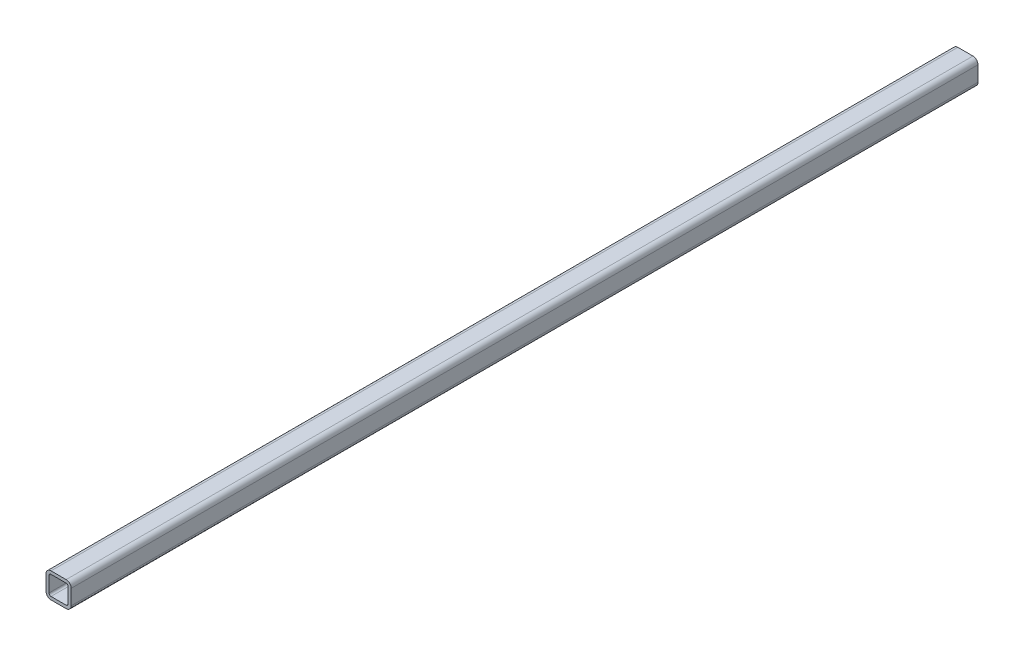
SolidWorks part; units mm, degrees
material "Plain Carbon Steel"
ref_plane "Front Plane" through (0, 0, 0) normal (0, 0, 1) x (1, 0, 0)
ref_plane "Top Plane" through (0, 0, 0) normal (0, 1, 0) x (1, 0, 0)
ref_plane "Right Plane" through (0, 0, 0) normal (1, 0, 0) x (0, 0, -1)
sketch "Sketch1" plane through (0, 0, 0) normal (0, 0, 1) x (1, 0, 0)
  line L0 (-9.5, 7.5) -> (-9.5, -7.5)
  line L1 (-7.5, -12.5) -> (7.5, -12.5)
  line L2 (-12.5, -7.5) -> (-12.5, 7.5)
  line L3 (-7.5, 12.5) -> (7.5, 12.5)
  line L4 (12.5, -7.5) -> (12.5, 7.5)
  line L5 (-12.5, -12.5) -> (12.5, 12.5) construction
  line L6 (-12.5, 12.5) -> (12.5, -12.5) construction
  line L7 (-7.5, -9.5) -> (7.5, -9.5)
  line L8 (9.5, -7.5) -> (9.5, 7.5)
  line L9 (7.5, 9.5) -> (-7.5, 9.5)
  arc A0 (-9.5, -7.5) -> (-7.5, -9.5) centre (-7.5, -7.5) ccw
  arc A1 (7.5, -9.5) -> (9.5, -7.5) centre (7.5, -7.5) ccw
  arc A2 (9.5, 7.5) -> (7.5, 9.5) centre (7.5, 7.5) ccw
  arc A3 (-9.5, 7.5) -> (-7.5, 9.5) centre (-7.5, 7.5) cw
  arc A4 (7.5, 12.5) -> (12.5, 7.5) centre (7.5, 7.5) cw
  arc A5 (7.5, -12.5) -> (12.5, -7.5) centre (7.5, -7.5) ccw
  arc A6 (-7.5, -12.5) -> (-12.5, -7.5) centre (-7.5, -7.5) cw
  arc A7 (-12.5, 7.5) -> (-7.5, 12.5) centre (-7.5, 7.5) cw
  point P0 (0, 0)
  point P12 (-9.5, -9.5)
  point P15 (9.5, -9.5)
  point P18 (9.5, 9.5)
  point P21 (-9.5, 9.5)
  dimension "D4" = 2
  dimension "D5" = 5
  dimension "D1" = 25
  dimension "D2" = 25
  dimension "D3" = 3
extrude "Boss-Extrude1" add sketch "Sketch1" along normal blind 900
